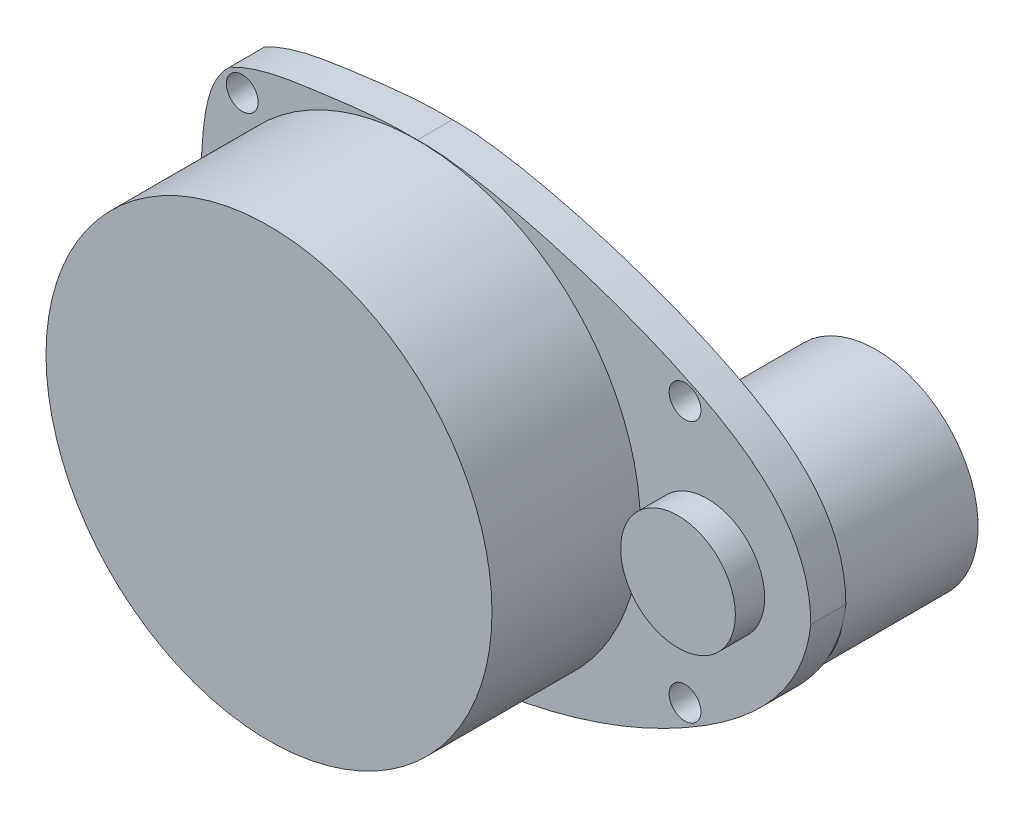
SolidWorks part; units mm, degrees
ref_plane "Plan de face" through (0, 0, 0) normal (0, 0, 1) x (1, 0, 0)
ref_plane "Plan de dessus" through (0, 0, 0) normal (0, 1, 0) x (1, 0, 0)
ref_plane "Plan de droite" through (0, 0, 0) normal (1, 0, 0) x (0, 0, -1)
sketch "Esquisse1" plane through (0, 0, 0) normal (0, 0, 1) x (1, 0, 0)
  line L1 (0, 0) -> (96.74, 0) construction
  line L2 (0, 0) -> (0, 70.28) construction
  line L3 (0, 70.28) -> (96.74, 70.28) construction
  line L4 (96.74, 0) -> (96.74, 70.28) construction
  circle A0 centre (7, 7.28) radius 2.5 construction
  circle A1 centre (7, 63.28) radius 2.5 construction
  circle A2 centre (77, 14.14) radius 2.5 construction
  circle A3 centre (77, 56.14) radius 2.5 construction
  circle A4 centre (35, 35.14) radius 35 construction
  spline S0 degree 3 poles (96.74, 35.14) (96.701, 46.9148) (76.6692, 62.5329) (43.1867, 70.4538) (35, 70.14) knots 0 0 0 0 0.420119 1 1 1 1
  spline S1 degree 3 poles (35, 70.14) (29.8992, 70.2961) (19.6297, 68.9898) (9.6415, 67.5142) (5.5136, 65.2901) knots 0 0 0 0 0.536067 1 1 1 1
  spline S2 degree 3 poles (5.5136, 65.2901) (1.6113, 61.6629) (1.2507, 49.9993) (-0.5354, 34.4269) (0.6549, 19.1657) (2.9225, 9.2712) (5.0922, 5.6644) knots 0 0 0 0 0.257205 0.505905 0.797009 1 1 1 1
  spline S3 degree 3 poles (96.74, 35.14) (95.5774, 24.4378) (74.6783, 6.3869) (40.0412, -1.5817) (14.1237, 0.6599) (5.0922, 5.6644) knots 0 0 0 0 0.293376 0.712148 1 1 1 1
  point P16 (96.74, 35.14)
  point P24 (94.7167, 27.9706)
  point P28 (94.7167, 44.1884)
  point P31 (0, 0)
  point P32 (0, 0)
  dimension "D5" = 5
  dimension "D6" = 5
  dimension "D7" = 5
  dimension "D8" = 5
  dimension "D12" = 70
  dimension "D1" = 96.74
  dimension "D2" = 70.28
  dimension "D3" = 56
  dimension "D4" = 7
  dimension "D9" = 77
  dimension "D10" = 42
  dimension "D11" = 35
  dimension "D13" = 35.14
  dimension "D14" = 21
  dimension "D15" = 7
extrude "Boss.-Extru.1" add sketch "Esquisse1" along normal blind 5.5
sketch "Esquisse3" plane through (0, 0, 5.5) normal (0, 0, 1) x (1, 0, 0)
  line L1 (0, 0) -> (96.74, 0) construction
  line L2 (0, 0) -> (0, 70.28) construction
  line L3 (0, 70.28) -> (96.74, 70.28) construction
  line L4 (96.74, 0) -> (96.74, 70.28) construction
  circle A0 centre (7.5, 62.78) radius 2.5
  circle A1 centre (7.5, 7.5) radius 2.5
  circle A2 centre (77, 14.64) radius 2.5
  circle A3 centre (77, 55.64) radius 2.5
  dimension "D5" = 5
  dimension "D6" = 5
  dimension "D7" = 5
  dimension "D8" = 5
  dimension "D1" = 70.28
  dimension "D2" = 96.74
  dimension "D3" = 7.5
  dimension "D4" = 7.5
  dimension "D9" = 7.5
  dimension "D10" = 7.5
  dimension "D11" = 77
  dimension "D12" = 20.5
  dimension "D13" = 77
  dimension "D14" = 20.5
extrude "Enlèv. mat.-Extru.1" cut sketch "Esquisse3" against normal up to surface (5.5 mm away) up to face at (35.5864, 44.0586, 0)
sketch "Esquisse4" plane through (0, 0, 5.5) normal (0, 0, 1) x (1, 0, 0)
  line L0 (0, 0) -> (0, 71.0408) construction
  line L1 (96.74, 35.14) -> (-4.2068, 35.14) construction
  circle A0 centre (80.5, 35.14) radius 9
  dimension "D2" = 18
  dimension "D1" = 80.5
extrude "Boss.-Extru.3" add sketch "Esquisse4" along normal blind 4.6
sketch "Esquisse2" plane through (0, 0, 5.5) normal (0, 0, 1) x (1, 0, 0)
  line L1 (0, 0) -> (96.74, 0) construction
  line L2 (0, 0) -> (0, 70.28) construction
  line L3 (0, 70.28) -> (96.74, 70.28) construction
  line L4 (96.74, 0) -> (96.74, 70.28) construction
  circle A0 centre (35, 35.1131) radius 35
  dimension "D5" = 70
  dimension "D2" = 96.74
  dimension "D3" = 70.28
  dimension "D4" = 35.1669
  dimension "D1" = 35
extrude "Boss.-Extru.2" add sketch "Esquisse2" along normal blind 23.3
sketch "Esquisse5" plane through (0, 0, 0) normal (0, 0, -1) x (-1, 0, 0)
  line L0 (0, 0) -> (0, 71.4877) construction
  line L1 (-96.74, 35.14) -> (9.6464, 35.14) construction
  circle A0 centre (-80.5, 35.14) radius 16
  dimension "D2" = 32
  dimension "D1" = 80.5
extrude "Boss.-Extru.4" add sketch "Esquisse5" along normal blind 21
equation "\"D6@Esquisse1\"=\"D5@Esquisse1\""
equation "\"D7@Esquisse1\"=\"D5@Esquisse1\""
equation "\"D8@Esquisse1\"=\"D5@Esquisse1\""
equation "\"D6@Esquisse3\"=\"D5@Esquisse3\""
equation "\"D7@Esquisse3\"=\"D5@Esquisse3\""
equation "\"D8@Esquisse3\"=\"D7@Esquisse3\""
